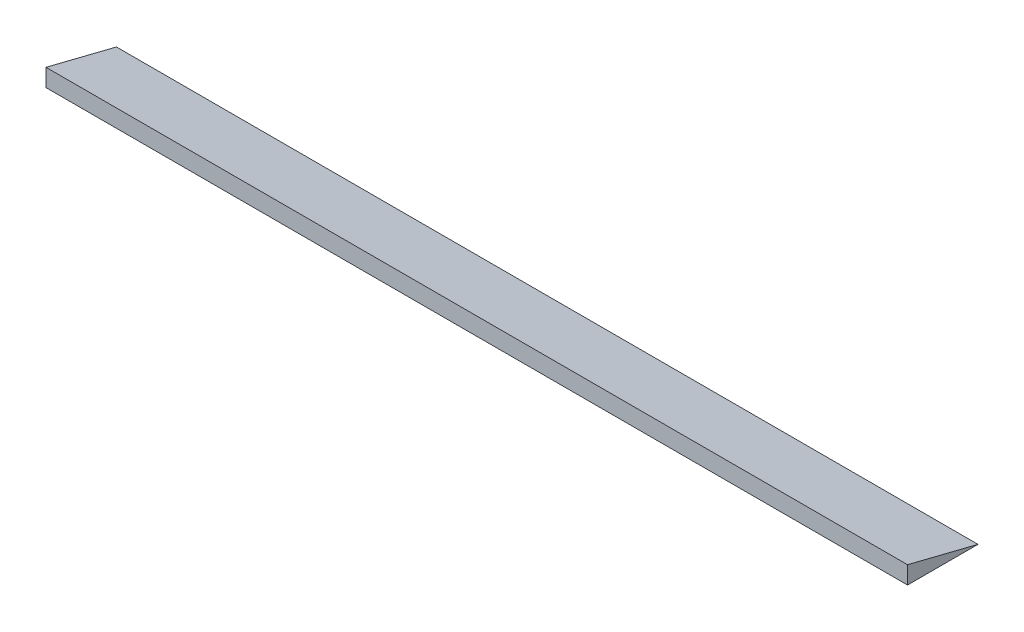
SolidWorks part; units mm, degrees
material "Balsa"
ref_plane "Front Plane" through (0, 0, 0) normal (0, 0, 1) x (1, 0, 0)
ref_plane "Top Plane" through (0, 0, 0) normal (0, 1, 0) x (1, 0, 0)
ref_plane "Right Plane" through (0, 0, 0) normal (1, 0, 0) x (0, 0, -1)
sketch "Sketch1" plane through (0, 0, 0) normal (1, 0, 0) x (0, 0, -1)
  line L0 (0, 0) -> (0, -12.7)
  line L1 (0, -12.7) -> (50.8, -12.7)
  line L2 (50.8, -12.7) -> (0, 0)
  dimension "D1" = 12.7
  dimension "D2" = 50.8
extrude "Boss-Extrude1" add sketch "Sketch1" along normal mid plane 621
